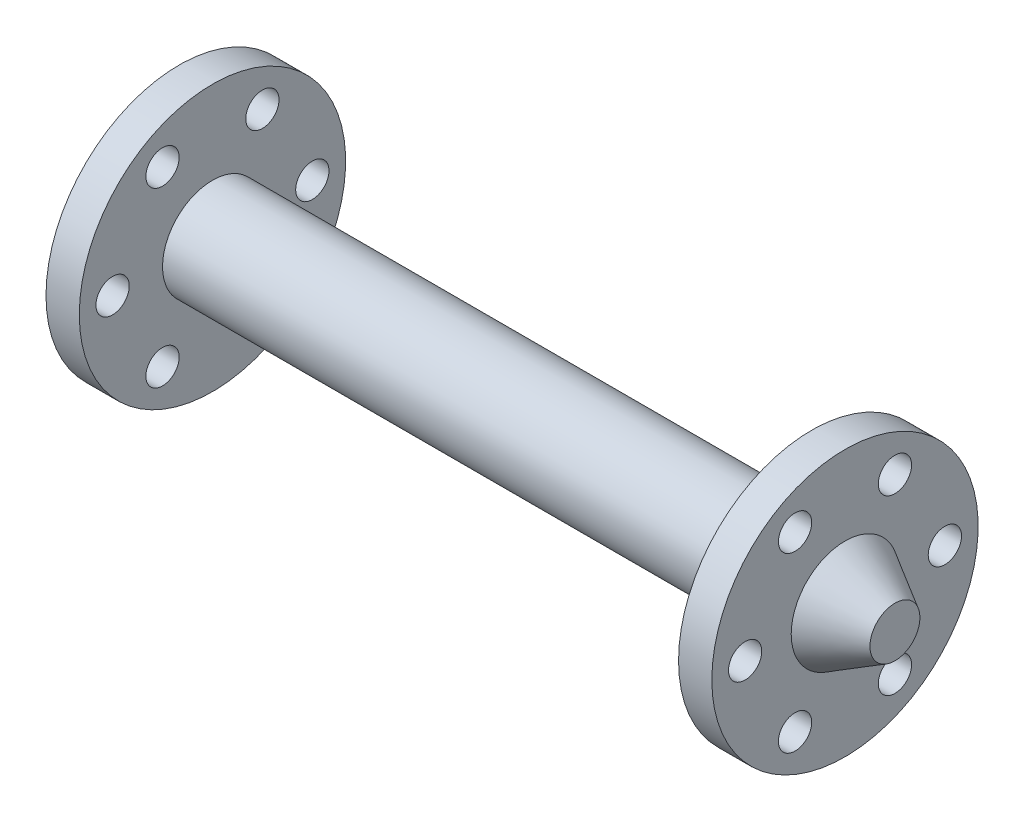
SolidWorks part; units mm, degrees
material "AISI 4340 Steel, normalized"
ref_plane "Front Plane" through (0, 0, 0) normal (0, 0, 1) x (1, 0, 0)
ref_plane "Top Plane" through (0, 0, 0) normal (0, 1, 0) x (1, 0, 0)
ref_plane "Right Plane" through (0, 0, 0) normal (1, 0, 0) x (0, 0, -1)
sketch "Sketch1" plane through (0, 0, 0) normal (0, 0, 1) x (1, 0, 0)
  line L0 (179.9962, -80) -> (179.9962, -30)
  line L1 (-230, 0) -> (-230, -15)
  line L2 (199.9962, -80) -> (179.9962, -80)
  line L3 (-199.9962, -32.3227) -> (-199.9962, -80)
  line L4 (-230, -15) -> (-199.9962, -32.3227)
  line L5 (-199.9962, -80) -> (-179.9962, -80)
  line L6 (230, -15) -> (199.9962, -32.3227)
  line L7 (-230, 0) -> (230, 0) construction
  line L8 (-179.9962, -30) -> (180.0038, -30)
  line L9 (-179.9962, -80) -> (-179.9962, -30)
  line L10 (199.9962, -32.3227) -> (199.9962, -80)
  line L11 (230, 0) -> (230, -15)
  point P4 (0, 0)
  dimension "D2" = 15
  dimension "D6" = 20
  dimension "D9" = 360
revolve "Revolve1" add sketch "Sketch1" angle 360 about L7
sketch "Sketch2" plane through (-199.9962, 0, 0) normal (-1, 0, 0) x (0, 0, 1)
  circle A1 centre (-60, 0) radius 10
  circle A3 centre (-30, 51.9615) radius 10
  circle A5 centre (30, 51.9615) radius 10
  circle A6 centre (0, 0) radius 60 construction
  circle A7 centre (60, 0) radius 10
  circle A8 centre (0, 0) radius 60 construction
  circle A9 centre (30, -51.9615) radius 10
  circle A10 centre (0, 0) radius 60 construction
  circle A11 centre (-30, -51.9615) radius 10
  point P22 (0, 0)
  dimension "D1" = 120
  dimension "D2" = 20
  dimension "D3" = 6
extrude "Cut-Extrude1" cut sketch "Sketch2" against normal blind 529
